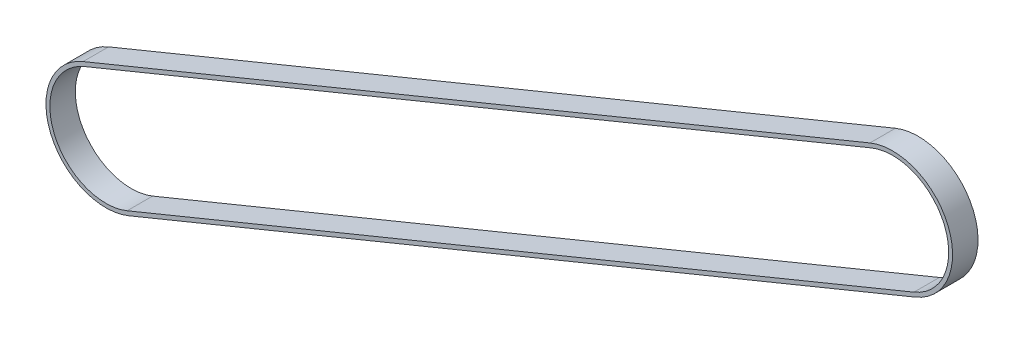
SolidWorks part; units mm, degrees
material "Natural Rubber"
ref_plane "Front Plane" through (0, 0, 0) normal (0, 0, 1) x (1, 0, 0)
ref_plane "Top Plane" through (0, 0, 0) normal (0, 1, 0) x (1, 0, 0)
ref_plane "Right Plane" through (0, 0, 0) normal (1, 0, 0) x (0, 0, -1)
sketch "Sketch2" plane through (0, 0, 0) normal (0, 0, 1) x (1, 0, 0)
  line L0 (0, 0) -> (1, 0) construction
  line L1 (0, 0) -> (0, 1) construction
  line L2 (12.53, -30.5286) -> (-451.0481, -220.7881)
  line L3 (-476.1071, -159.7304) -> (-12.529, 30.5291)
  arc A0 (-12.529, 30.5291) -> (12.53, -30.5286) centre (0.0005, 0.0003) cw
  arc A1 (-451.0481, -220.7881) -> (-476.1071, -159.7304) centre (-463.5776, -190.2593) cw
sketch "Sketch3" plane through (0, 0, 0) normal (0, 0, 1) x (1, 0, 0)
  line L0 (-476.1071, -159.7304) -> (-12.529, 30.5291) construction
  line L1 (-476.1071, -159.7304) -> (-12.529, 30.5291)
ref_plane "Plane1" through (-12.529, 30.5291, 0) normal (0.9251, 0.3797, 0) x (0, 0, -1)
sketch "Sketch4" plane through (-12.529, 30.5291, 0) normal (0.9251, 0.3797, 0) x (0, 0, -1)
  line L1 (0, 0) -> (-15, 0)
  line L2 (0, 0) -> (0, 2.286)
  line L3 (0, 2.286) -> (-15, 2.286)
  line L4 (-15, 0) -> (-15, 2.286)
  dimension "D1" = 15
  dimension "D2" = 2.286
sweep "Sweep1" add profiles "Sketch4" path "Sketch2"
